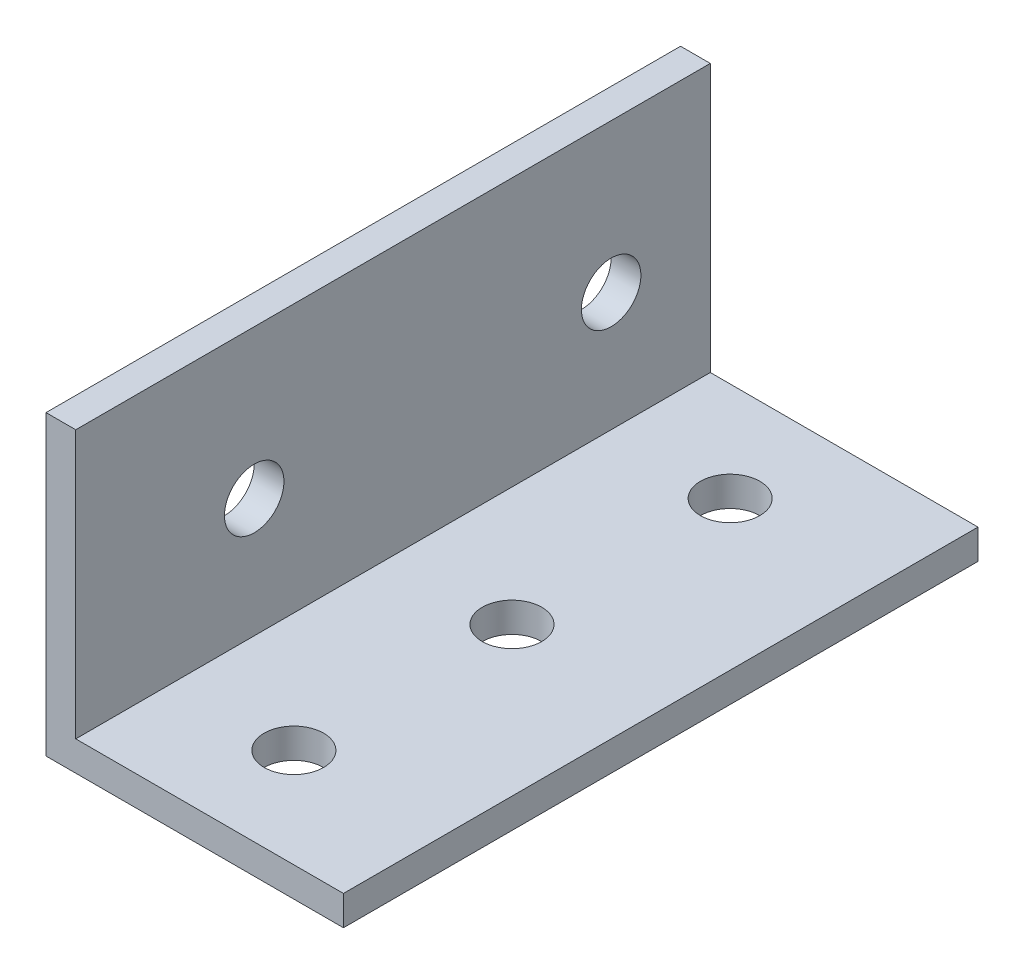
SolidWorks part; units mm, degrees
ref_plane "Plan de face" through (0, 0, 0) normal (0, 0, 1) x (1, 0, 0)
ref_plane "Plan de dessus" through (0, 0, 0) normal (0, 1, 0) x (1, 0, 0)
ref_plane "Plan de droite" through (0, 0, 0) normal (1, 0, 0) x (0, 0, -1)
sketch "Esquisse1" plane through (0, 0, 0) normal (0, 0, 1) x (1, 0, 0)
  line L0 (-12.5379, 4.3312) -> (-12.5379, -10.6688)
  line L1 (-12.5379, -10.6688) -> (2.4621, -10.6688)
  line L2 (2.4621, -10.6688) -> (2.4621, -9.1688)
  line L3 (2.4621, -9.1688) -> (-11.0379, -9.1688)
  line L4 (-11.0379, -9.1688) -> (-11.0379, 4.3312)
  line L5 (-11.0379, 4.3312) -> (-12.5379, 4.3312)
  dimension "D1" = 1.5
  dimension "D2" = 1.5
  dimension "D3" = 15
  dimension "D4" = 15
extrude "Extrusion1" add sketch "Esquisse1" along normal blind 32
sketch "Esquisse2" plane through (-12.5379, 0, 0) normal (-1, 0, 0) x (0, 0, 1)
  line L0 (32, 4.3312) -> (0, 4.3312) construction
  line L1 (0, 4.3312) -> (0, -10.6688) construction
  circle A0 centre (23, -3.1688) radius 1.5
  circle A1 centre (5, -3.1688) radius 1.5
  dimension "D1" = 7.5
  dimension "D2" = 7.5
  dimension "D3" = 5
  dimension "D4" = 18
extrude "Extrusion2" cut sketch "Esquisse2" against normal blind 25
sketch "Esquisse3" plane through (0, -10.6688, 0) normal (0, -1, 0) x (1, 0, 0)
  line L0 (-12.5379, 0) -> (2.4621, 0) construction
  line L1 (2.4621, 32) -> (2.4621, 0) construction
  line L2 (-12.5379, 32) -> (2.4621, 32) construction
  circle A0 centre (-5.0379, 5) radius 1.5
  circle A1 centre (-5.0379, 27) radius 1.5
  circle A2 centre (-5.0379, 16) radius 1.5
  dimension "D1" = 5
  dimension "D3" = 5
  dimension "D4" = 11
  dimension "D2" = 7.5
extrude "Extrusion3" cut sketch "Esquisse3" against normal blind 25
